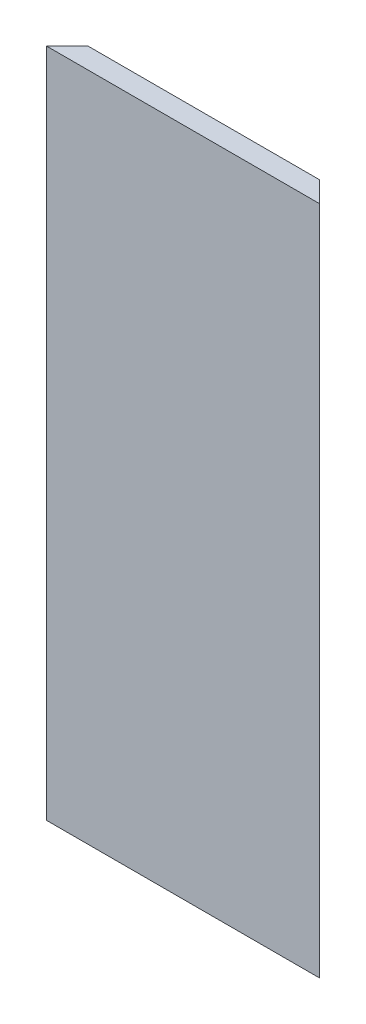
SolidWorks part; units mm, degrees
ref_plane "Front Plane" through (0, 0, 0) normal (0, 0, 1) x (1, 0, 0)
ref_plane "Top Plane" through (0, 0, 0) normal (0, 1, 0) x (1, 0, 0)
ref_plane "Right Plane" through (0, 0, 0) normal (1, 0, 0) x (0, 0, -1)
sketch "Sketch1" plane through (0, 0, 0) normal (0, 1, 0) x (1, 0, 0)
  line L0 (-11.2, -0.85) -> (-9.5, 0.85)
  line L1 (-9.5, 0.85) -> (9.5, 0.85)
  line L3 (-11.2, -0.85) -> (11.2, -0.85)
  line L5 (-9.6199, 0.7301) -> (11.2, -0.85) construction
  line L6 (-11.2, -0.85) -> (9.6199, 0.7301) construction
  line L8 (-11.2, 0.85) -> (-11.2033, 0.8487)
  line L9 (11.2, -0.85) -> (9.5, 0.85)
  point P0 (0, 0)
  dimension "D2" = 1.7
extrude "Boss-Extrude1" add sketch "Sketch1" along normal blind 55 contours L1 L9 L3 L0
